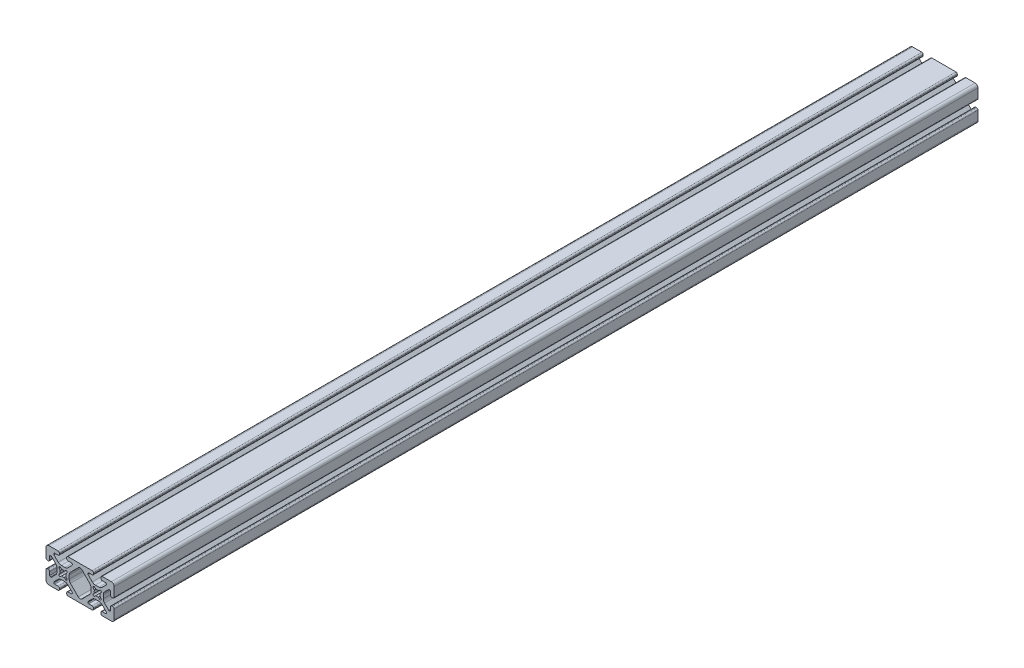
SolidWorks part; units mm, degrees
material "6063-T6"
ref_plane "Front Plane" through (0, 0, 0) normal (0, 0, 1) x (1, 0, 0)
ref_plane "Top Plane" through (0, 0, 0) normal (0, 1, 0) x (1, 0, 0)
ref_plane "Right Plane" through (0, 0, 0) normal (1, 0, 0) x (0, 0, -1)
ref_plane "Plane1" through (0, 0, -25.4) normal (0, 0, -1) x (-1, 0, 0)
sketch "Sketch1" plane through (0, 0, -25.4) normal (0, 0, -1) x (-1, 0, 0)
  line L0 (5.3872, 29.8392) -> (14.1109, 21.1155)
  line L1 (14.1109, 16.9845) -> (5.3872, 8.2608)
  line L2 (2.0285, 6.8697) -> (-2.0285, 6.8697)
  line L3 (-5.3872, 8.2608) -> (-14.1109, 16.9845)
  line L4 (-14.1109, 21.1155) -> (-5.3872, 29.8392)
  line L5 (-2.0285, 31.2303) -> (2.0285, 31.2303)
  line L6 (1.4014, 3.0179) -> (2.7269, 4.3433)
  line L7 (4.3433, 2.7269) -> (3.0179, 1.4014)
  line L8 (3.0179, -1.4014) -> (4.3433, -2.7269)
  line L9 (2.7269, -4.3433) -> (1.4014, -3.0179)
  line L10 (-1.4014, -3.0179) -> (-2.7269, -4.3433)
  line L11 (-4.3433, -2.7269) -> (-3.0179, -1.4014)
  line L12 (-3.0179, 1.4014) -> (-4.3433, 2.7269)
  line L13 (-2.7269, 4.3433) -> (-1.4014, 3.0179)
  line L14 (3.0179, 36.6986) -> (4.3433, 35.3731)
  line L15 (2.7269, 33.7567) -> (1.4014, 35.0821)
  line L16 (-1.4014, 35.0821) -> (-2.7269, 33.7567)
  line L17 (-4.3433, 35.3731) -> (-3.0179, 36.6986)
  line L18 (-3.0179, 39.5014) -> (-4.3433, 40.8269)
  line L19 (-2.7269, 42.4433) -> (-1.4014, 41.1179)
  line L20 (1.4014, 41.1179) -> (2.7269, 42.4433)
  line L21 (4.3433, 40.8269) -> (3.0179, 39.5014)
  line L22 (17.4752, 34.036) -> (16.5608, 34.036)
  line L23 (14.986, 32.4612) -> (14.986, 28.702)
  line L24 (14.097, 27.813) -> (13.5289, 27.813)
  line L25 (12.9003, 28.0734) -> (8.2608, 32.7128)
  line L26 (6.8697, 36.0715) -> (6.8697, 40.1285)
  line L27 (8.2608, 43.4872) -> (12.9003, 48.1266)
  line L28 (13.5289, 48.387) -> (14.097, 48.387)
  line L29 (14.986, 47.498) -> (14.986, 43.7388)
  line L30 (16.5608, 42.164) -> (17.4752, 42.164)
  line L31 (19.05, 43.7388) -> (19.05, 53.975)
  line L32 (15.875, 57.15) -> (5.6388, 57.15)
  line L33 (4.064, 55.5752) -> (4.064, 54.6608)
  line L34 (5.6388, 53.086) -> (9.398, 53.086)
  line L35 (10.287, 52.197) -> (10.287, 51.6289)
  line L36 (10.0266, 51.0003) -> (5.3872, 46.3608)
  line L37 (2.0285, 44.9697) -> (-2.0285, 44.9697)
  line L38 (-5.3872, 46.3608) -> (-10.0266, 51.0003)
  line L39 (-10.287, 51.6289) -> (-10.287, 52.197)
  line L40 (-9.398, 53.086) -> (-5.6388, 53.086)
  line L41 (-4.064, 54.6608) -> (-4.064, 55.5752)
  line L42 (-5.6388, 57.15) -> (-15.875, 57.15)
  line L43 (-19.05, 53.975) -> (-19.05, 43.7388)
  line L44 (-17.4752, 42.164) -> (-16.5608, 42.164)
  line L45 (-14.986, 43.7388) -> (-14.986, 47.498)
  line L46 (-14.097, 48.387) -> (-13.5289, 48.387)
  line L47 (-12.9003, 48.1266) -> (-8.2608, 43.4872)
  line L48 (-6.8697, 40.1285) -> (-6.8697, 36.0715)
  line L49 (-8.2608, 32.7128) -> (-12.9003, 28.0734)
  line L50 (-13.5289, 27.813) -> (-14.097, 27.813)
  line L51 (-14.986, 28.702) -> (-14.986, 32.4612)
  line L52 (-16.5608, 34.036) -> (-17.4752, 34.036)
  line L53 (-19.05, 32.4612) -> (-19.05, 5.6388)
  line L54 (-17.4752, 4.064) -> (-16.5608, 4.064)
  line L55 (-14.986, 5.6388) -> (-14.986, 9.398)
  line L56 (-14.097, 10.287) -> (-13.5289, 10.287)
  line L57 (-12.9003, 10.0266) -> (-8.2608, 5.3872)
  line L58 (-6.8697, 2.0285) -> (-6.8697, -2.0285)
  line L59 (-8.2608, -5.3872) -> (-12.9003, -10.0266)
  line L60 (-13.5289, -10.287) -> (-14.097, -10.287)
  line L61 (-14.986, -9.398) -> (-14.986, -5.6388)
  line L62 (-16.5608, -4.064) -> (-17.4752, -4.064)
  line L63 (-19.05, -5.6388) -> (-19.05, -15.875)
  line L64 (-15.875, -19.05) -> (-5.6388, -19.05)
  line L65 (-4.064, -17.4752) -> (-4.064, -16.5608)
  line L66 (-5.6388, -14.986) -> (-9.398, -14.986)
  line L67 (-10.287, -14.097) -> (-10.287, -13.5289)
  line L68 (-10.0266, -12.9003) -> (-5.3872, -8.2608)
  line L69 (-2.0285, -6.8697) -> (2.0285, -6.8697)
  line L70 (5.3872, -8.2608) -> (10.0266, -12.9003)
  line L71 (10.287, -13.5289) -> (10.287, -14.097)
  line L72 (9.398, -14.986) -> (5.6388, -14.986)
  line L73 (4.064, -16.5608) -> (4.064, -17.4752)
  line L74 (5.6388, -19.05) -> (15.875, -19.05)
  line L75 (19.05, -15.875) -> (19.05, -5.6388)
  line L76 (17.4752, -4.064) -> (16.5608, -4.064)
  line L77 (14.986, -5.6388) -> (14.986, -9.398)
  line L78 (14.097, -10.287) -> (13.5289, -10.287)
  line L79 (12.9003, -10.0266) -> (8.2608, -5.3872)
  line L80 (6.8697, -2.0285) -> (6.8697, 2.0285)
  line L81 (8.2608, 5.3872) -> (12.9003, 10.0266)
  line L82 (13.5289, 10.287) -> (14.097, 10.287)
  line L83 (14.986, 9.398) -> (14.986, 5.6388)
  line L84 (16.5608, 4.064) -> (17.4752, 4.064)
  line L85 (19.05, 5.6388) -> (19.05, 32.4612)
  arc A0 (14.1109, 21.1155) -> (14.1109, 16.9845) centre (12.0454, 19.05) cw
  arc A1 (5.3872, 8.2608) -> (2.0285, 6.8697) centre (2.0285, 11.6195) cw
  arc A2 (-2.0285, 6.8697) -> (-5.3872, 8.2608) centre (-2.0285, 11.6195) cw
  arc A3 (-14.1109, 16.9845) -> (-14.1109, 21.1155) centre (-12.0454, 19.05) cw
  arc A4 (-5.3872, 29.8392) -> (-2.0285, 31.2303) centre (-2.0285, 26.4805) cw
  arc A5 (2.0285, 31.2303) -> (5.3872, 29.8392) centre (2.0285, 26.4805) cw
  arc A6 (2.7269, 4.3433) -> (4.3433, 2.7269) centre (3.5351, 3.5351) cw
  arc A7 (3.0179, 1.4014) -> (3.0179, -1.4014) centre (0, 0) cw
  arc A8 (4.3433, -2.7269) -> (2.7269, -4.3433) centre (3.5351, -3.5351) cw
  arc A9 (1.4014, -3.0179) -> (-1.4014, -3.0179) centre (0, 0) cw
  arc A10 (-2.7269, -4.3433) -> (-4.3433, -2.7269) centre (-3.5351, -3.5351) cw
  arc A11 (-3.0179, -1.4014) -> (-3.0179, 1.4014) centre (0, 0) cw
  arc A12 (-4.3433, 2.7269) -> (-2.7269, 4.3433) centre (-3.5351, 3.5351) cw
  arc A13 (-1.4014, 3.0179) -> (1.4014, 3.0179) centre (0, 0) cw
  arc A14 (4.3433, 35.3731) -> (2.7269, 33.7567) centre (3.5351, 34.5649) cw
  arc A15 (1.4014, 35.0821) -> (-1.4014, 35.0821) centre (0, 38.1) cw
  arc A16 (-2.7269, 33.7567) -> (-4.3433, 35.3731) centre (-3.5351, 34.5649) cw
  arc A17 (-3.0179, 36.6986) -> (-3.0179, 39.5014) centre (0, 38.1) cw
  arc A18 (-4.3433, 40.8269) -> (-2.7269, 42.4433) centre (-3.5351, 41.6351) cw
  arc A19 (-1.4014, 41.1179) -> (1.4014, 41.1179) centre (0, 38.1) cw
  arc A20 (2.7269, 42.4433) -> (4.3433, 40.8269) centre (3.5351, 41.6351) cw
  arc A21 (3.0179, 39.5014) -> (3.0179, 36.6986) centre (0, 38.1) cw
  arc A22 (19.05, 32.4612) -> (17.4752, 34.036) centre (17.4752, 32.4612) ccw
  arc A23 (16.5608, 34.036) -> (14.986, 32.4612) centre (16.5608, 32.4612) ccw
  arc A24 (14.986, 28.702) -> (14.097, 27.813) centre (14.097, 28.702) cw
  arc A25 (13.5289, 27.813) -> (12.9003, 28.0734) centre (13.5289, 28.702) cw
  arc A26 (8.2608, 32.7128) -> (6.8697, 36.0715) centre (11.6195, 36.0715) cw
  arc A27 (6.8697, 40.1285) -> (8.2608, 43.4872) centre (11.6195, 40.1285) cw
  arc A28 (12.9003, 48.1266) -> (13.5289, 48.387) centre (13.5289, 47.498) cw
  arc A29 (14.097, 48.387) -> (14.986, 47.498) centre (14.097, 47.498) cw
  arc A30 (14.986, 43.7388) -> (16.5608, 42.164) centre (16.5608, 43.7388) ccw
  arc A31 (17.4752, 42.164) -> (19.05, 43.7388) centre (17.4752, 43.7388) ccw
  arc A32 (19.05, 53.975) -> (15.875, 57.15) centre (15.875, 53.975) ccw
  arc A33 (5.6388, 57.15) -> (4.064, 55.5752) centre (5.6388, 55.5752) ccw
  arc A34 (4.064, 54.6608) -> (5.6388, 53.086) centre (5.6388, 54.6608) ccw
  arc A35 (9.398, 53.086) -> (10.287, 52.197) centre (9.398, 52.197) cw
  arc A36 (10.287, 51.6289) -> (10.0266, 51.0003) centre (9.398, 51.6289) cw
  arc A37 (5.3872, 46.3608) -> (2.0285, 44.9697) centre (2.0285, 49.7195) cw
  arc A38 (-2.0285, 44.9697) -> (-5.3872, 46.3608) centre (-2.0285, 49.7195) cw
  arc A39 (-10.0266, 51.0003) -> (-10.287, 51.6289) centre (-9.398, 51.6289) cw
  arc A40 (-10.287, 52.197) -> (-9.398, 53.086) centre (-9.398, 52.197) cw
  arc A41 (-5.6388, 53.086) -> (-4.064, 54.6608) centre (-5.6388, 54.6608) ccw
  arc A42 (-4.064, 55.5752) -> (-5.6388, 57.15) centre (-5.6388, 55.5752) ccw
  arc A43 (-15.875, 57.15) -> (-19.05, 53.975) centre (-15.875, 53.975) ccw
  arc A44 (-19.05, 43.7388) -> (-17.4752, 42.164) centre (-17.4752, 43.7388) ccw
  arc A45 (-16.5608, 42.164) -> (-14.986, 43.7388) centre (-16.5608, 43.7388) ccw
  arc A46 (-14.986, 47.498) -> (-14.097, 48.387) centre (-14.097, 47.498) cw
  arc A47 (-13.5289, 48.387) -> (-12.9003, 48.1266) centre (-13.5289, 47.498) cw
  arc A48 (-8.2608, 43.4872) -> (-6.8697, 40.1285) centre (-11.6195, 40.1285) cw
  arc A49 (-6.8697, 36.0715) -> (-8.2608, 32.7128) centre (-11.6195, 36.0715) cw
  arc A50 (-12.9003, 28.0734) -> (-13.5289, 27.813) centre (-13.5289, 28.702) cw
  arc A51 (-14.097, 27.813) -> (-14.986, 28.702) centre (-14.097, 28.702) cw
  arc A52 (-14.986, 32.4612) -> (-16.5608, 34.036) centre (-16.5608, 32.4612) ccw
  arc A53 (-17.4752, 34.036) -> (-19.05, 32.4612) centre (-17.4752, 32.4612) ccw
  arc A54 (-19.05, 5.6388) -> (-17.4752, 4.064) centre (-17.4752, 5.6388) ccw
  arc A55 (-16.5608, 4.064) -> (-14.986, 5.6388) centre (-16.5608, 5.6388) ccw
  arc A56 (-14.986, 9.398) -> (-14.097, 10.287) centre (-14.097, 9.398) cw
  arc A57 (-13.5289, 10.287) -> (-12.9003, 10.0266) centre (-13.5289, 9.398) cw
  arc A58 (-8.2608, 5.3872) -> (-6.8697, 2.0285) centre (-11.6195, 2.0285) cw
  arc A59 (-6.8697, -2.0285) -> (-8.2608, -5.3872) centre (-11.6195, -2.0285) cw
  arc A60 (-12.9003, -10.0266) -> (-13.5289, -10.287) centre (-13.5289, -9.398) cw
  arc A61 (-14.097, -10.287) -> (-14.986, -9.398) centre (-14.097, -9.398) cw
  arc A62 (-14.986, -5.6388) -> (-16.5608, -4.064) centre (-16.5608, -5.6388) ccw
  arc A63 (-17.4752, -4.064) -> (-19.05, -5.6388) centre (-17.4752, -5.6388) ccw
  arc A64 (-19.05, -15.875) -> (-15.875, -19.05) centre (-15.875, -15.875) ccw
  arc A65 (-5.6388, -19.05) -> (-4.064, -17.4752) centre (-5.6388, -17.4752) ccw
  arc A66 (-4.064, -16.5608) -> (-5.6388, -14.986) centre (-5.6388, -16.5608) ccw
  arc A67 (-9.398, -14.986) -> (-10.287, -14.097) centre (-9.398, -14.097) cw
  arc A68 (-10.287, -13.5289) -> (-10.0266, -12.9003) centre (-9.398, -13.5289) cw
  arc A69 (-5.3872, -8.2608) -> (-2.0285, -6.8697) centre (-2.0285, -11.6195) cw
  arc A70 (2.0285, -6.8697) -> (5.3872, -8.2608) centre (2.0285, -11.6195) cw
  arc A71 (10.0266, -12.9003) -> (10.287, -13.5289) centre (9.398, -13.5289) cw
  arc A72 (10.287, -14.097) -> (9.398, -14.986) centre (9.398, -14.097) cw
  arc A73 (5.6388, -14.986) -> (4.064, -16.5608) centre (5.6388, -16.5608) ccw
  arc A74 (4.064, -17.4752) -> (5.6388, -19.05) centre (5.6388, -17.4752) ccw
  arc A75 (15.875, -19.05) -> (19.05, -15.875) centre (15.875, -15.875) ccw
  arc A76 (19.05, -5.6388) -> (17.4752, -4.064) centre (17.4752, -5.6388) ccw
  arc A77 (16.5608, -4.064) -> (14.986, -5.6388) centre (16.5608, -5.6388) ccw
  arc A78 (14.986, -9.398) -> (14.097, -10.287) centre (14.097, -9.398) cw
  arc A79 (13.5289, -10.287) -> (12.9003, -10.0266) centre (13.5289, -9.398) cw
  arc A80 (8.2608, -5.3872) -> (6.8697, -2.0285) centre (11.6195, -2.0285) cw
  arc A81 (6.8697, 2.0285) -> (8.2608, 5.3872) centre (11.6195, 2.0285) cw
  arc A82 (12.9003, 10.0266) -> (13.5289, 10.287) centre (13.5289, 9.398) cw
  arc A83 (14.097, 10.287) -> (14.986, 9.398) centre (14.097, 9.398) cw
  arc A84 (14.986, 5.6388) -> (16.5608, 4.064) centre (16.5608, 5.6388) ccw
  arc A85 (17.4752, 4.064) -> (19.05, 5.6388) centre (17.4752, 5.6388) ccw
extrude "Boss-Extrude1" add sketch "Sketch1" against normal blind 965.2
move or copy body "Body-Move/Copy2" bodies to move or copy 103 copy no rotation origin (0, 7.9166, 0) rotation axis (0, 0, 1) rotation angle 90
